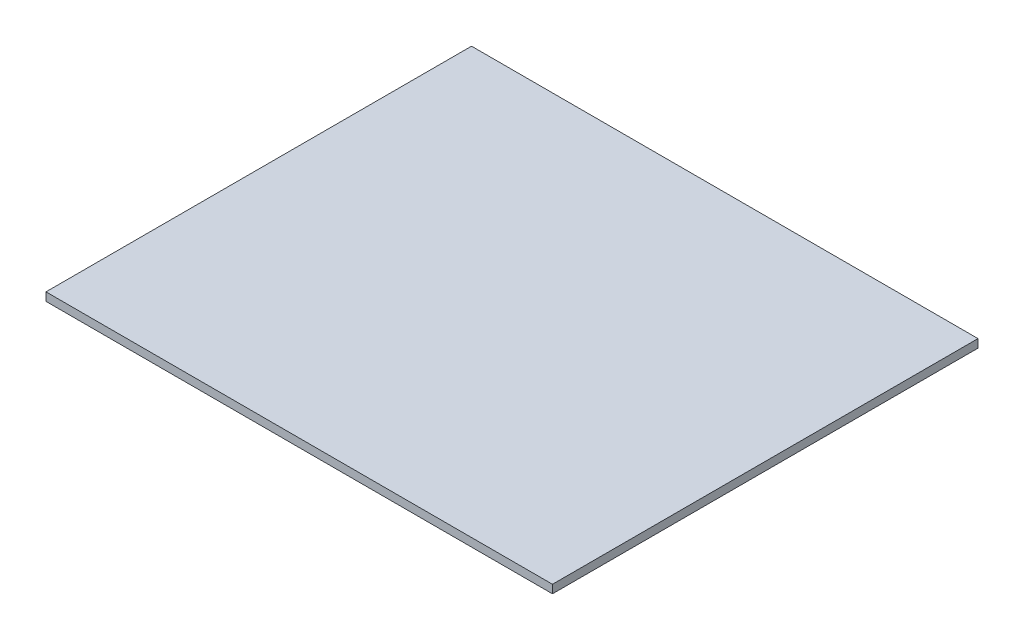
SolidWorks part; units mm, degrees
ref_plane "Front Plane" through (0, 0, 0) normal (0, 0, 1) x (1, 0, 0)
ref_plane "Top Plane" through (0, 0, 0) normal (0, 1, 0) x (1, 0, 0)
ref_plane "Right Plane" through (0, 0, 0) normal (1, 0, 0) x (0, 0, -1)
sketch "Sketch2" plane through (0, 0, 0) normal (0, 1, 0) x (1, 0, 0)
  line L1 (0, 0) -> (488, 0)
  line L2 (0, 0) -> (0, 410)
  line L3 (0, 410) -> (488, 410)
  line L4 (488, 0) -> (488, 410)
  dimension "D1" = 488
  dimension "D2" = 410
extrude "Boss-Extrude1" add sketch "Sketch2" along normal blind 8
